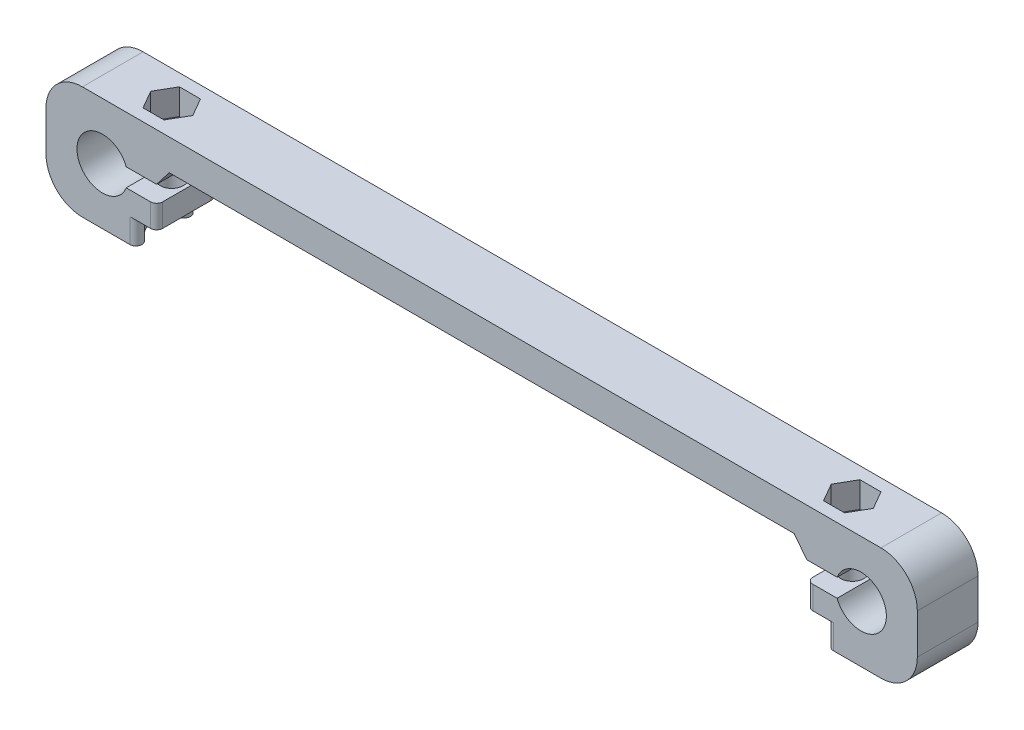
SolidWorks part; units mm, degrees
ref_plane "Alzado" through (0, 0, 0) normal (0, 0, 1) x (1, 0, 0)
ref_plane "Planta" through (0, 0, 0) normal (0, 1, 0) x (1, 0, 0)
ref_plane "Vista lateral" through (0, 0, 0) normal (1, 0, 0) x (0, 0, -1)
sketch "Croquis1" plane through (0, 0, 0) normal (0, 0, 1) x (1, 0, 0)
  line L0 (-62.5, 0) -> (62.5, 0) construction
  line L1 (-65.8, 9.3) -> (65.8, 9.3)
  line L2 (-71.8, 3.3) -> (-71.8, -3.3)
  line L3 (-65.8, -9.3) -> (65.8, -9.3)
  line L4 (71.8, 3.3) -> (71.8, -3.3)
  line L5 (-71.8, 9.3) -> (71.8, -9.3) construction
  line L6 (-71.8, -9.3) -> (71.8, 9.3) construction
  line L7 (-59.5641, 1.5) -> (-46.2, 1.5)
  line L8 (-46.2, 1.5) -> (-46.2, -9.3)
  line L9 (48.2, -1.5) -> (48.2, -9.3)
  line L10 (0, 9.3) -> (0, -9.3) construction
  line L11 (-60.6533, -1.5) -> (-48.2, -1.5)
  line L12 (-48.2, -1.5) -> (-48.2, -9.3)
  line L13 (46.2, 1.5) -> (46.2, -9.3)
  line L14 (60.6533, -1.5) -> (48.2, -1.5)
  line L15 (59.5641, 1.5) -> (46.2, 1.5)
  circle A0 centre (-62.5, 0) radius 4.2
  circle A1 centre (62.5, 0) radius 4.2
  arc A2 (65.8, 9.3) -> (71.8, 3.3) centre (65.8, 3.3) cw
  arc A3 (71.8, -3.3) -> (65.8, -9.3) centre (65.8, -3.3) cw
  arc A4 (-71.8, -3.3) -> (-65.8, -9.3) centre (-65.8, -3.3) ccw
  arc A5 (-65.8, 9.3) -> (-71.8, 3.3) centre (-65.8, 3.3) ccw
  point P0 (0, 0)
  dimension "D3" = 8.4
  dimension "D4" = 8.4
  dimension "D7" = 6
  dimension "D8" = 1.5
  dimension "D1" = 125
  dimension "D2" = 62.5
  dimension "D5" = 143.6
  dimension "D6" = 18.6
  dimension "D9" = 1.5
  dimension "D10" = 9.3
  dimension "D11" = 16.3
  dimension "D12" = 2
extrude "Saliente-Extruir1" add sketch "Croquis1" along normal blind 10
sketch "Croquis2" plane through (0, 1.5, 0) normal (0, -1, 0) x (1, 0, 0)
  line L1 (0, 10) -> (0, 0) construction
  line L3 (-58.577, 10) -> (-58.577, 0) construction
  line L4 (-48.2, 10) -> (-48.2, 0) construction
  circle A0 centre (-56.077, 5) radius 1.9
  circle A1 centre (56.077, 5) radius 1.9
  dimension "D2" = 3.8
  dimension "D1" = 2.5
  dimension "D3" = 7.877
extrude "Cortar-Extruir1" cut sketch "Croquis2" against normal mid plane 50
sketch "Croquis7" plane through (0, 0, 0) normal (0, 0, -1) x (-1, 0, 0)
  line L0 (62.5, 4.2) -> (-62.5, 4.2) construction
  line L1 (51.5, 4.2) -> (53.577, 1.5)
  line L2 (58.577, 1.5) -> (46.2, 1.5) construction
  line L3 (51.5, 4.2) -> (-51.5, 4.2)
  line L4 (-51.5, 4.2) -> (-53.577, 1.5)
  line L5 (-58.577, 1.5) -> (-46.2, 1.5) construction
  line L6 (-53.577, 1.5) -> (-46.2, 1.5)
  line L7 (-46.2, 1.5) -> (-46.2, -9.3)
  line L8 (-46.2, -9.3) -> (46.2, -9.3)
  line L9 (46.2, -9.3) -> (46.2, 1.5)
  line L10 (46.2, 1.5) -> (53.577, 1.5)
  arc A0 (58.577, -1.5) -> (58.577, 1.5) centre (62.5, 0) ccw construction
  arc A1 (-58.577, 1.5) -> (-58.577, -1.5) centre (-62.5, 0) ccw construction
  dimension "D1" = 11
  dimension "D2" = 5
  dimension "D3" = 11
  dimension "D4" = 5
extrude "Cortar-Extruir5" cut sketch "Croquis7" against normal through all
sketch "Croquis8" plane through (0, 0, 0) normal (0, 0, -1) x (-1, 0, 0)
  line L0 (65.8, -9.3) -> (48.2, -9.3) construction
  line L1 (48.2, -1.5) -> (53.577, -1.5)
  line L2 (48.2, -1.5) -> (48.2, -9.3)
  line L3 (48.2, -9.3) -> (53.577, -9.3)
  line L4 (53.577, -1.5) -> (53.577, -9.3)
  line L5 (-48.2, -9.3) -> (-65.8, -9.3) construction
  line L6 (-48.2, -1.5) -> (-53.577, -1.5)
  line L7 (-48.2, -1.5) -> (-48.2, -9.3)
  line L8 (-48.2, -9.3) -> (-53.577, -9.3)
  line L9 (-53.577, -1.5) -> (-53.577, -9.3)
  dimension "D1" = 5
  dimension "D2" = 5
extrude "Cortar-Extruir6" cut sketch "Croquis8" against normal through all
sketch "Croquis5" plane through (0, 9.3, 0) normal (0, 1, 0) x (1, 0, 0)
  line L1 (-52.6129, -5) -> (-54.3449, -2)
  line L2 (-54.3449, -2) -> (-57.809, -2)
  line L3 (-57.809, -2) -> (-59.5411, -5)
  line L4 (-59.5411, -5) -> (-57.809, -8)
  line L5 (-57.809, -8) -> (-54.3449, -8)
  line L6 (-54.3449, -8) -> (-52.6129, -5)
  line L7 (59.5411, -5) -> (57.809, -2)
  line L8 (57.809, -2) -> (54.3449, -2)
  line L9 (54.3449, -2) -> (52.6129, -5)
  line L10 (52.6129, -5) -> (54.3449, -8)
  line L11 (54.3449, -8) -> (57.809, -8)
  line L12 (57.809, -8) -> (59.5411, -5)
  circle A0 centre (-56.077, -5) radius 3 construction
  circle A1 centre (56.077, -5) radius 3 construction
  dimension "D1" = 6
  dimension "D2" = 6
sketch "Croquis10" plane through (0, -9.3, 0) normal (0, -1, 0) x (1, 0, 0)
  line L0 (-58.3216, 7.2447) -> (-51.076, 14.4903)
  line L1 (-58.3216, 2.7553) -> (-52.9831, -2.5832)
  line L2 (-65.8, 0) -> (-53.577, 0) construction
  line L3 (-65.8, 10) -> (-53.577, 10) construction
  line L4 (-51.076, 14.4903) -> (-52.9831, -2.5832)
  line L5 (0, 0) -> (0, 43.1294) construction
  line L6 (51.076, 14.4903) -> (52.9831, -2.5832)
  line L7 (58.3216, 2.7553) -> (52.9831, -2.5832)
  line L8 (58.3216, 7.2447) -> (51.076, 14.4903)
  circle A0 centre (56.077, 5) radius 3.1744
  circle A1 centre (-56.077, 5) radius 3.1744
  circle M1 centre (56.077, 5) radius 1.9
  line M2 (65.8, 10) -> (53.577, 10)
  line M3 (53.577, 10) -> (53.577, 0)
  line M4 (53.577, 0) -> (65.8, 0)
  dimension "D1" = 45
  dimension "D2" = 45
extrude "Cortar-Extruir7" cut sketch "Croquis5" against normal blind 4.25
extrude "Cortar-Extruir8" cut sketch "Croquis10" against normal blind 4 contours A1 L1 L4 L0 | A1 | A0 L8 L6 L7 M3 M2 M4 | A0 L8 M3 M2 | A0 M3 M1 | A0 M3 | L7 A0 M3 M4
fillet "Redondeo1" radius 1 8 edges at (-53.577, -3.4, 10) (-53.577, -3.4, 0) (53.577, -3.4, 0) (53.577, -3.4, 10) (55.5663, -7.3, 0) (55.5663, -7.3, 10) (-55.5663, -7.3, 0) (-55.5663, -7.3, 10)
sketch "Croquis11" plane through (0, 4.2, 0) normal (0, -1, 0) x (1, 0, 0)
  line L7 (-51.5, 10) -> (51.5, 10) construction
  line L8 (-51.5, 0) -> (51.5, 0) construction
  line L9 (20.735, -7) -> (-20.735, -7)
  line L10 (20.735, -7) -> (20.735, 7)
  line L11 (20.735, 7) -> (-20.735, 7)
  line L12 (-20.735, -7) -> (-20.735, 7)
  line L13 (20.735, -7) -> (-20.735, 7) construction
  line L14 (20.735, 7) -> (-20.735, -7) construction
  point P6 (0, 0)
  dimension "D3" = 3
  dimension "D4" = 41.47
extrude "Cortar-Extruir9" cut sketch "Croquis11" against normal blind 1.2
fillet "Redondeo2" radius 0.2 5 edges at (-20.735, 4.8, 0) (20.735, 4.8, 0) (20.735, 4.2, 3.5) (0, 4.2, 7) (-20.735, 4.2, 3.5)
